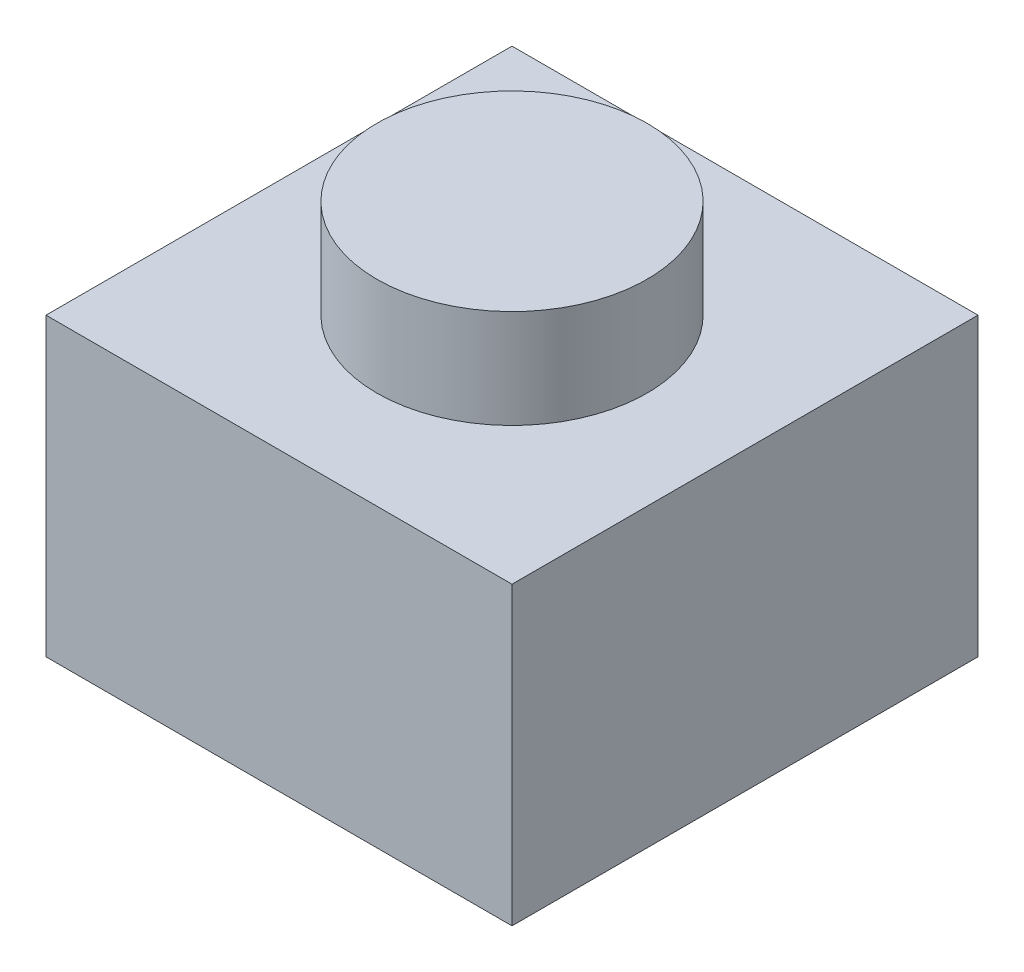
SolidWorks part; units mm, degrees
ref_plane "Front Plane" through (0, 0, 0) normal (0, 0, 1) x (1, 0, 0)
ref_plane "Top Plane" through (0, 0, 0) normal (0, 1, 0) x (1, 0, 0)
ref_plane "Right Plane" through (0, 0, 0) normal (1, 0, 0) x (0, 0, -1)
sketch "Sketch1" plane through (0, 0, 0) normal (0, 1, 0) x (1, 0, 0)
  line L1 (-3, -3) -> (3, -3)
  line L2 (-3, -3) -> (-3, 3)
  line L3 (-3, 3) -> (3, 3)
  line L4 (3, -3) -> (3, 3)
  line L5 (-3, -3) -> (3, 3) construction
  line L6 (-3, 3) -> (3, -3) construction
  point P0 (0, 0)
  dimension "D1" = 6
  dimension "D2" = 6
extrude "Boss-Extrude1" add sketch "Sketch1" along normal blind 3.81
sketch "Sketch2" plane through (0, 3.81, 0) normal (0, 1, 0) x (1, 0, 0)
  circle A0 centre (0, 0) radius 1.7399
  dimension "D1" = 3.4798
extrude "Boss-Extrude2" add sketch "Sketch2" along normal blind 1.27
